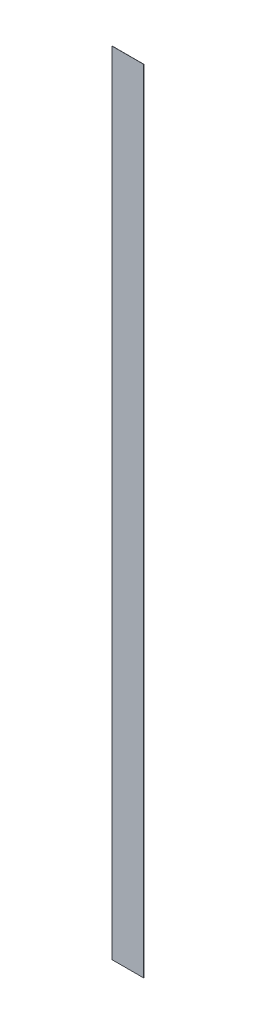
SolidWorks part; units mm, degrees
material "Ferro duttile"
ref_plane "Piano frontale" through (0, 0, 0) normal (0, 0, 1) x (1, 0, 0)
ref_plane "Piano superiore" through (0, 0, 0) normal (0, 1, 0) x (1, 0, 0)
ref_plane "Piano destro" through (0, 0, 0) normal (1, 0, 0) x (0, 0, -1)
sketch "Schizzo1" plane through (0, 0, 0) normal (0, 0, 1) x (1, 0, 0)
  line L1 (0, 0) -> (-3000, 0)
  line L2 (0, 0) -> (0, 75000)
  line L3 (0, 75000) -> (-3000, 75000)
  line L4 (-3000, 0) -> (-3000, 75000)
  dimension "D1" = 3000
  dimension "D2" = 75000
extrude "Estrusione-Estrusione1" add sketch "Schizzo1" along normal blind 15
